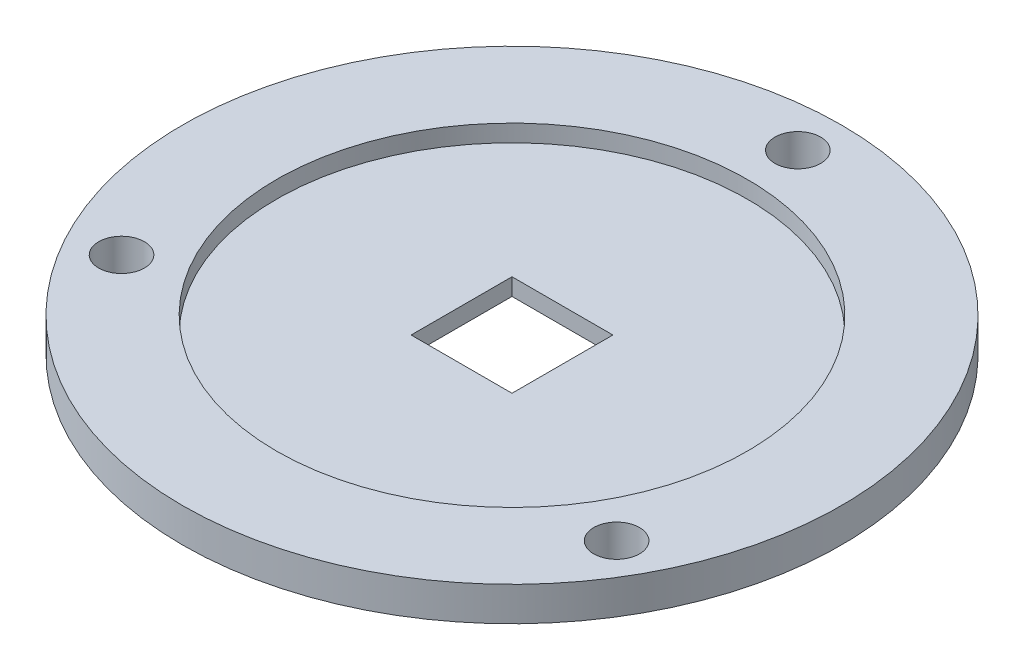
SolidWorks part; units mm, degrees
ref_plane "Front" through (0, 0, 0) normal (0, 0, 1) x (1, 0, 0)
ref_plane "Top" through (0, 0, 0) normal (0, 1, 0) x (1, 0, 0)
ref_plane "Right" through (0, 0, 0) normal (1, 0, 0) x (0, 0, -1)
sketch "Sketch1" plane through (0, 0, 0) normal (0, 1, 0) x (1, 0, 0)
  circle A0 centre (0, 0) radius 24.5
  dimension "D1" = 49
extrude "Boss-Extrude1" add sketch "Sketch1" along normal blind 2.54
sketch "Sketch2" plane through (0, 2.54, 0) normal (0, 1, 0) x (1, 0, 0)
  line L0 (0, 0) -> (0, 21.25) construction
  line L1 (0, 0) -> (-18.403, -10.625) construction
  line L2 (0, 0) -> (18.403, -10.625) construction
  line L3 (0, 17.5) -> (0, 25) construction
  circle A0 centre (0, 0) radius 17.5
  circle A2 centre (0, 0) radius 21.25 construction
  circle A3 centre (0, 0) radius 25
  point P11 (0, 21.25)
  dimension "D1" = 35
  dimension "D4" = 50
  dimension "D2" = 120
  dimension "D3" = 120
hole_wizard "M3 Clearance Hole1" positions "3DSketch1" profile "Sketch3" hole size "M3" standard "ANSI Metric"
sketch3d "3DSketch1"
  point P0 (-18.403, 2.54, 10.625)
  point P3 (18.403, 2.54, 10.625)
  point P6 (0, 2.54, -21.25)
sketch "Sketch3" plane through (-18.403, 2.54, 10.625) normal (1, 0, 0) x (0, 0, 1)
  line L0 (0, 0) -> (0, 3.5605)
  line L1 (0, 3.5605) -> (1.7, 2.539)
  line L2 (1.7, 2.539) -> (1.7, 0)
  line L5 (1.7, 0) -> (0, 0)
  line L10 (0, 3.5605) -> (-1.7, 2.539) construction
  line L11 (0, -6.35) -> (0, 107.95) construction
  dimension "Hole Dia." = 3.4
  dimension "Hole Depth" = 2.539
  dimension "Drill Angle" = 118
sketch "Sketch4" plane through (0, 2.54, 0) normal (0, 1, 0) x (1, 0, 0)
  circle A0 centre (0, 0) radius 17.5
  dimension "D1" = 35
extrude "Cut-Extrude1" cut sketch "Sketch4" against normal blind 1.27
sketch "Sketch5" plane through (0, 1.27, 0) normal (0, 1, 0) x (1, 0, 0)
  line L0 (-17.5, 0) -> (17.5, 0) construction
  line L2 (-3.75, -3.75) -> (3.75, -3.75)
  line L3 (-3.75, -3.75) -> (-3.75, 3.75)
  line L4 (-3.75, 3.75) -> (3.75, 3.75)
  line L5 (3.75, -3.75) -> (3.75, 3.75)
  circle A0 centre (0, 0) radius 17.5 construction
  circle A1 centre (0, 0) radius 17.5 construction
  point P11 (0, 3.75)
  point P14 (-3.75, 0)
  dimension "D1" = 7.5
  dimension "D3" = 7.5
extrude "Cut-Extrude2" cut sketch "Sketch5" against normal up to surface (1.27 mm away) up to face at (-18.403, 0, 12.325)
